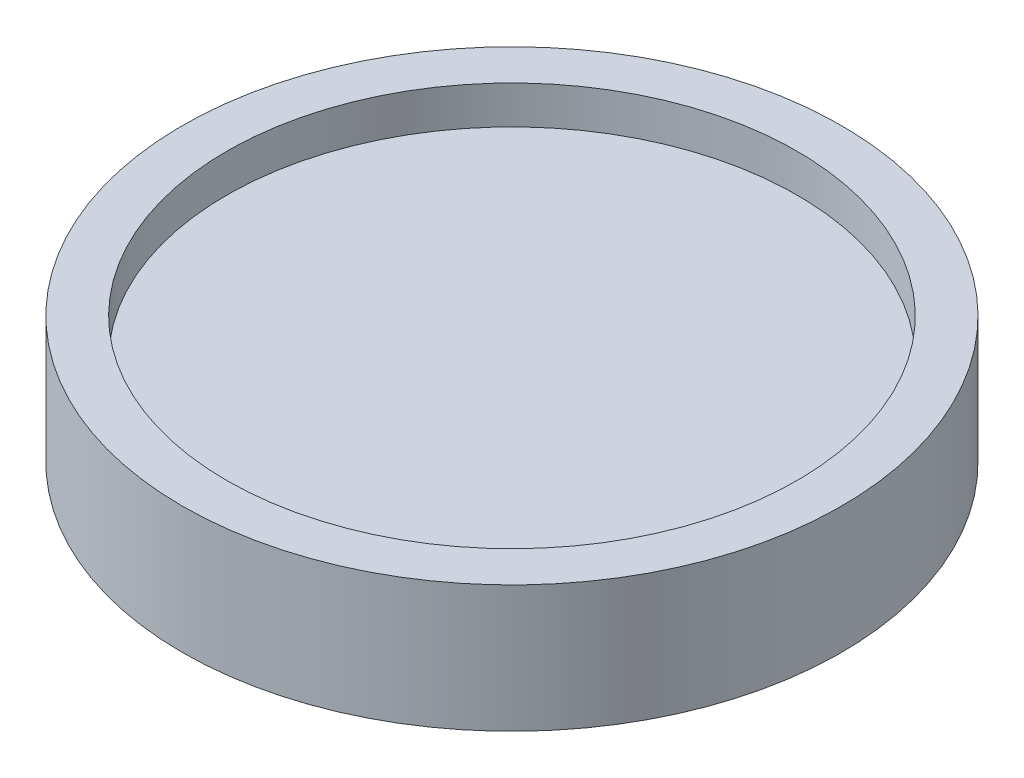
SolidWorks part; units mm, degrees
ref_plane "Front Plane" through (0, 0, 0) normal (0, 0, 1) x (1, 0, 0)
ref_plane "Top Plane" through (0, 0, 0) normal (0, 1, 0) x (1, 0, 0)
ref_plane "Right Plane" through (0, 0, 0) normal (1, 0, 0) x (0, 0, -1)
sketch "Sketch1" plane through (0, 0, 0) normal (0, 1, 0) x (1, 0, 0)
  circle A0 centre (0, 0) radius 33.02
  dimension "D1" = 66.04
extrude "Boss-Extrude1" add sketch "Sketch1" along normal blind 12.7
sketch "Sketch2" plane through (0, 12.7, 0) normal (0, 1, 0) x (1, 0, 0)
  circle A0 centre (0, 0) radius 28.575
  dimension "D1" = 57.15
extrude "Cut-Extrude1" cut sketch "Sketch2" against normal blind 3.81
